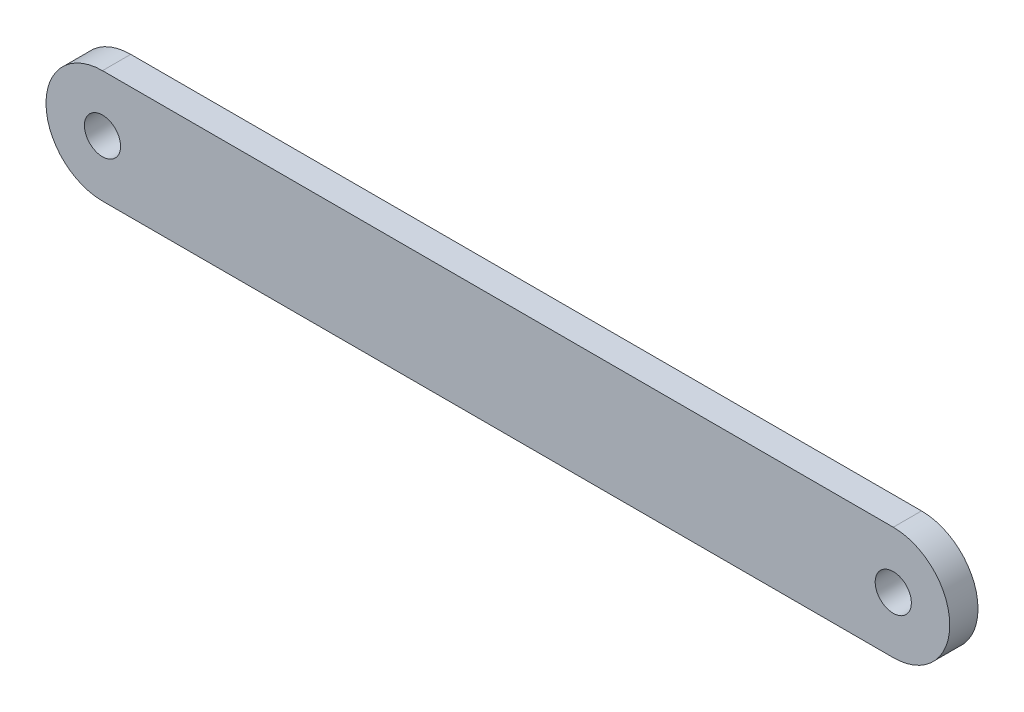
SolidWorks part; units mm, degrees
ref_plane "Front Plane" through (0, 0, 0) normal (0, 0, 1) x (1, 0, 0)
ref_plane "Top Plane" through (0, 0, 0) normal (0, 1, 0) x (1, 0, 0)
ref_plane "Right Plane" through (0, 0, 0) normal (1, 0, 0) x (0, 0, -1)
sketch "Sketch1" plane through (0, 0, 0) normal (0, 0, 1) x (1, 0, 0)
  line L2 (0, 0) -> (-88.9, 0) construction
  line L3 (0, -6.35) -> (-88.9, -6.35)
  line L4 (0, 6.35) -> (-88.9, 6.35)
  arc A4 (0, -6.35) -> (0, 6.35) centre (0, 0) ccw
  arc A5 (-88.9, 6.35) -> (-88.9, -6.35) centre (-88.9, 0) ccw
  circle A6 centre (0, 0) radius 2.032
  circle A7 centre (-88.9, 0) radius 2.032
  point P2 (-44.45, 0)
  dimension "D1" = 6.35
  dimension "D3" = 4.064
  dimension "D2" = 88.9
extrude "Boss-Extrude1" add sketch "Sketch1" along normal blind 3.175
